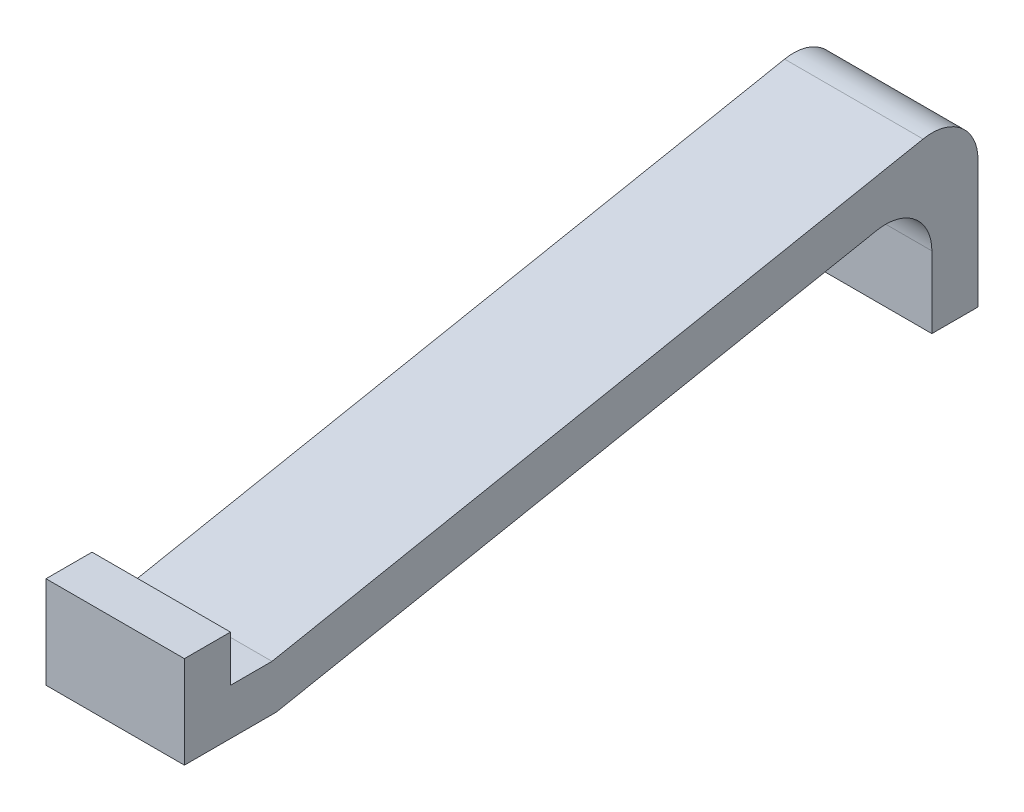
SolidWorks part; units mm, degrees
ref_plane "Alzado" through (0, 0, 0) normal (0, 0, 1) x (1, 0, 0)
ref_plane "Planta" through (0, 0, 0) normal (0, 1, 0) x (1, 0, 0)
ref_plane "Vista lateral" through (0, 0, 0) normal (1, 0, 0) x (0, 0, -1)
sketch "Croquis1" plane through (0, 0, 0) normal (0, 1, 0) x (1, 0, 0)
  line L1 (-117.5, -117.5) -> (117.5, -117.5) construction
  line L2 (-117.5, -117.5) -> (-117.5, 117.5) construction
  line L3 (-117.5, 117.5) -> (117.5, 117.5) construction
  line L4 (117.5, -117.5) -> (117.5, 117.5) construction
  line L5 (-117.5, -117.5) -> (117.5, 117.5) construction
  line L6 (-117.5, 117.5) -> (117.5, -117.5) construction
  point P0 (0, 0)
  dimension "D1" = 235
  dimension "D2" = 235
sketch "Croquis2" plane through (0, 0, 0) normal (1, 0, 0) x (0, 0, -1)
  line L0 (-102.2606, 0) -> (-82.3073, 0)
  line L1 (-117.5, 0) -> (117.5, 0) construction
  line L2 (-82.3073, 0) -> (47.8289, 25.3526)
  line L3 (59.7411, 15.5372) -> (59.7411, 0)
  line L4 (117.5, 0) -> (-117.5, 0) construction
  line L5 (59.7411, 0) -> (69.7411, 0)
  line L6 (69.7411, 0) -> (69.7411, 27.6733)
  line L7 (57.8289, 37.4888) -> (-83.2724, 10)
  line L8 (-83.2724, 10) -> (-92.284, 10)
  line L9 (-92.284, 10) -> (-92.284, 20)
  line L10 (-92.284, 20) -> (-102.2606, 20)
  line L11 (-102.2606, 20) -> (-102.2606, 0)
  arc A0 (69.7411, 27.6733) -> (57.8289, 37.4888) centre (59.7411, 27.6733) ccw
  arc A1 (47.8289, 25.3526) -> (59.7411, 15.5372) centre (49.7411, 15.5372) cw
  dimension "D5" = 10
  dimension "D1" = 10
  dimension "D2" = 10
  dimension "D3" = 10
  dimension "D4" = 10
extrude "Saliente-Extruir1" add sketch "Croquis2" along normal blind 30
